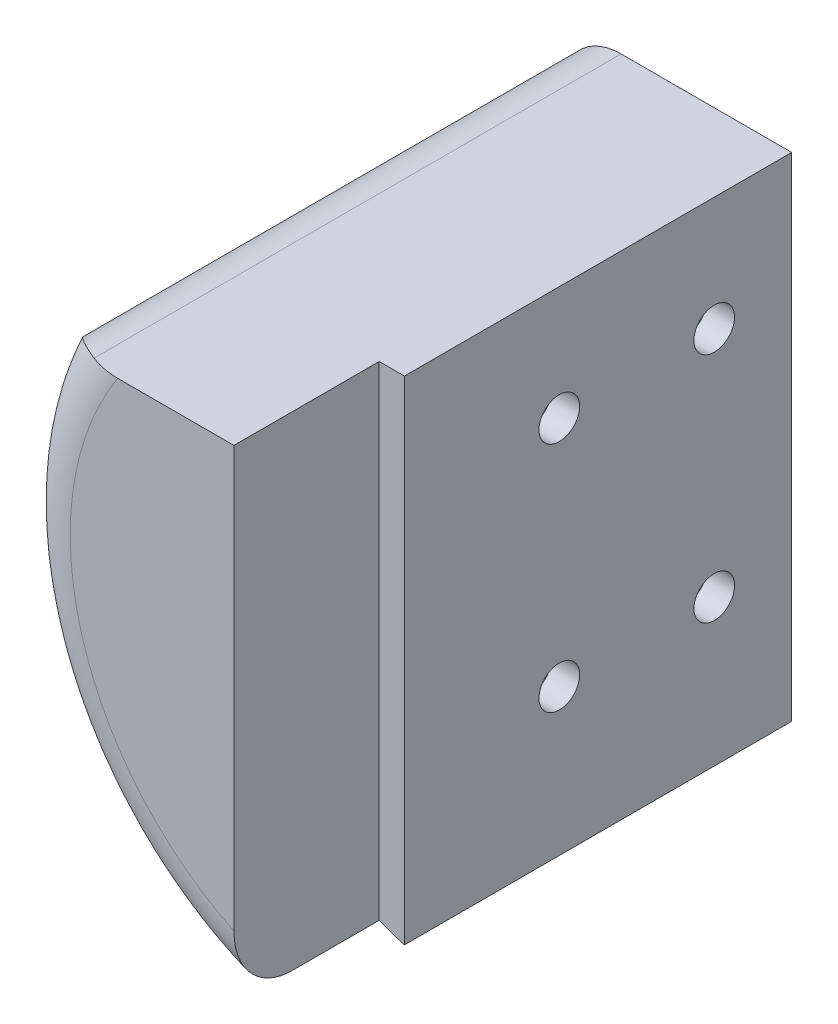
SolidWorks part; units mm, degrees
ref_plane "Front" through (0, 0, 0) normal (0, 0, 1) x (1, 0, 0)
ref_plane "Top" through (0, 0, 0) normal (0, 1, 0) x (1, 0, 0)
ref_plane "Right" through (0, 0, 0) normal (1, 0, 0) x (0, 0, -1)
sketch "Sketch1" plane through (0, 0, 0) normal (0, 0, 1) x (1, 0, 0)
  line L4 (-10.5, 16.4414) -> (-10.5, -34.4347)
  line L5 (-10.5, 16.4414) -> (-32.0262, 16.4414)
  arc A0 (-32.0262, 16.4414) -> (-10.5, -34.4347) centre (0, 0) ccw
extrude "Boss-Extrude1" add sketch "Sketch1" along normal blind 55
sketch "Sketch2" plane through (-10.5, 0, 0) normal (1, 0, 0) x (0, 0, -1)
  line L1 (-55, -34.4347) -> (0, -34.4347) construction
  line L2 (-40, -34.4347) -> (-55, -34.4347)
  line L3 (-55, -34.4347) -> (-55, 16.4414)
  line L4 (-55, -34.4347) -> (-55, 16.4414) construction
  line L5 (-55, 16.4414) -> (-40, 16.4414)
  line L6 (-55, 16.4414) -> (0, 16.4414) construction
  line L7 (-40, 16.4414) -> (-40, -34.4347)
extrude "Cut-Extrude1" cut sketch "Sketch2" against normal blind 2.6
sketch "Sketch3" plane through (-10.5, 0, 0) normal (1, 0, 0) x (0, 0, -1)
  circle A0 centre (-8, 4.6814) radius 2.1
  circle A1 centre (-24, 4.6814) radius 2.1
  circle A2 centre (-24, -19.3186) radius 2.1
  circle A3 centre (-8, -19.3186) radius 2.1
  dimension "D1" = 2
  dimension "D2" = 2
extrude "Cut-Extrude2" cut sketch "Sketch3" against normal blind 32.6
fillet "Fillet2" radius 6 2 edges at (-32.0262, 16.4414, 27.5) (-33.6664, -12.7504, 55)
ref_plane "Plane1" through (-36, 0, 0) normal (-1, 0, 0) x (0, 0, 1)
sketch "Sketch4" plane through (-36, 0, 0) normal (-1, 0, 0) x (0, 0, 1)
  circle A0 centre (8, 4.6814) radius 3.65
  circle A1 centre (24, 4.6814) radius 3.65
  circle A2 centre (24, -19.3186) radius 3.65
  circle A3 centre (8, -19.3186) radius 3.65
  dimension "D1" = 2
extrude "Cut-Extrude3" cut sketch "Sketch4" against normal blind 22.6
